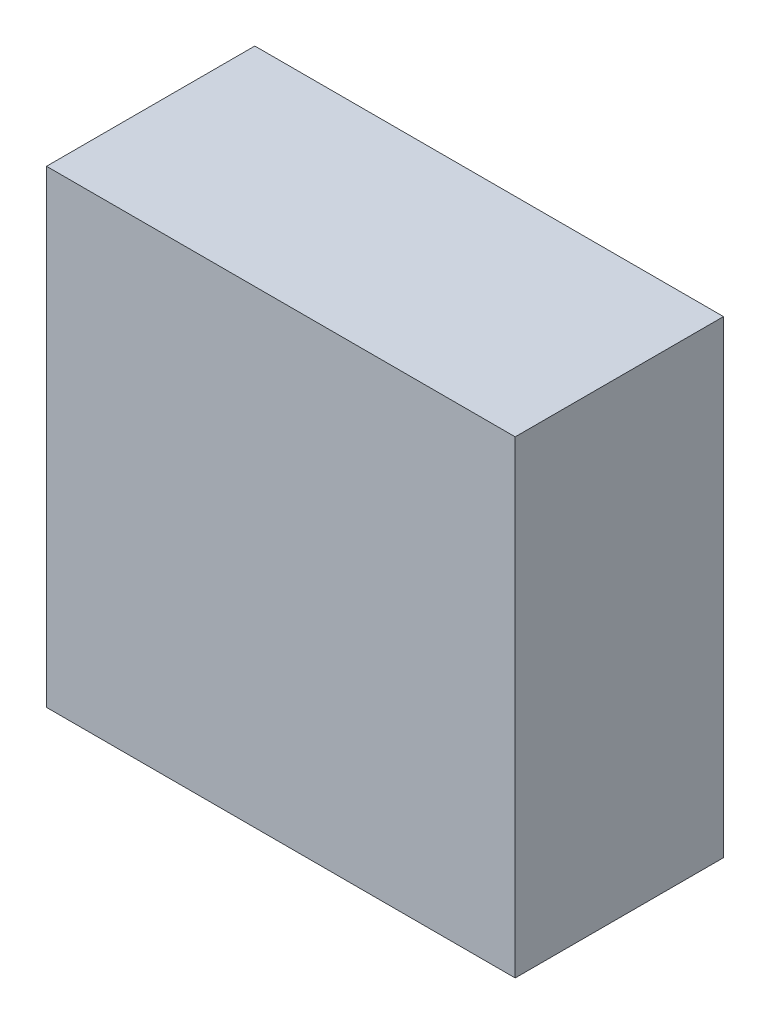
SolidWorks part; units mm, degrees
ref_plane "前视基准面" through (0, 0, 0) normal (0, 0, 1) x (1, 0, 0)
ref_plane "上视基准面" through (0, 0, 0) normal (0, 1, 0) x (1, 0, 0)
ref_plane "右视基准面" through (0, 0, 0) normal (1, 0, 0) x (0, 0, -1)
sketch "草图1" plane through (0, 0, 0) normal (0, 0, 1) x (1, 0, 0)
  line L1 (-36, -36) -> (36, -36)
  line L2 (-36, -36) -> (-36, 36)
  line L3 (-36, 36) -> (36, 36)
  line L4 (36, -36) -> (36, 36)
  line L5 (-36, -36) -> (36, 36) construction
  line L6 (-36, 36) -> (36, -36) construction
  point P0 (0, 0)
  dimension "D1" = 72
  dimension "D2" = 72
extrude "凸台-拉伸1" add sketch "草图1" along normal blind 32
